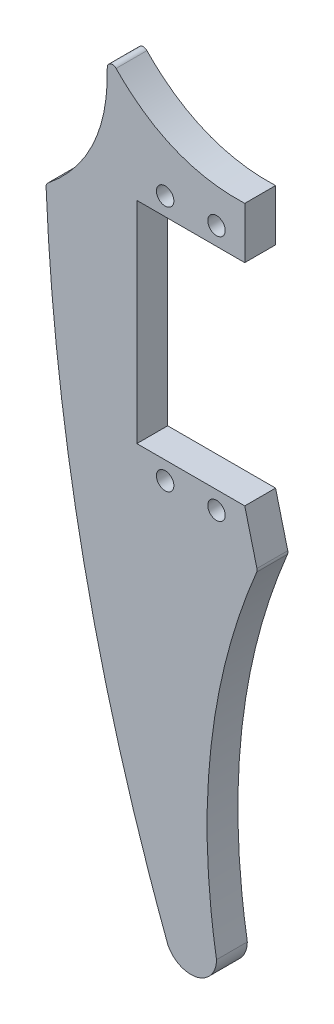
SolidWorks part; units mm, degrees
ref_plane "Front Plane" through (0, 0, 0) normal (0, 0, 1) x (1, 0, 0)
ref_plane "Top Plane" through (0, 0, 0) normal (0, 1, 0) x (1, 0, 0)
ref_plane "Right Plane" through (0, 0, 0) normal (1, 0, 0) x (0, 0, -1)
sketch "Sketch1" plane through (0, 0, 0) normal (0, 0, 1) x (1, 0, 0)
  line L0 (0, 20.5) -> (0, 10.25) construction
  line L1 (-10.5, -20.5) -> (10.5, -20.5)
  line L2 (-10.5, -20.5) -> (-10.5, 20.5)
  line L3 (-10.5, 20.5) -> (10.5, 20.5)
  line L4 (10.5, -20.5) -> (10.5, 20.5)
  line L5 (-10.5, -20.5) -> (10.5, 20.5) construction
  line L6 (-10.5, 20.5) -> (10.5, -20.5) construction
  line L7 (0, 10.25) -> (0, -99.75) construction
  line L8 (10.5, -20.5) -> (12.9541, -30.1942)
  line L9 (10.5, 20.5) -> (10.5, 30.5)
  circle A0 centre (-5, 24) radius 1.7
  circle A1 centre (5, 24) radius 1.7
  circle A2 centre (5, -24) radius 1.7
  circle A3 centre (-5, -24) radius 1.7
  circle A4 centre (0, -99.75) radius 5
  spline S0 degree 2 poles (10.5, 30.5) (-5.4634, 29.9016) (-16.4308, 42.8026) knots 0 0 0 1 1 1
  spline S1 degree 2 poles (-28.1926, 14.4749) (-25.711, -45.5894) (-4.433, -102.0628) knots 0 0 0 1 1 1
  spline S2 degree 2 poles (-16.4308, 42.8026) (-14.7841, 25.0085) (-28.1926, 14.4749) knots 0 0 0 1 1 1
  spline S3 degree 2 poles (12.9541, -30.1942) (-1.0702, -63.2681) (5, -99.75) knots 0 0 0 1 1 1
  point P0 (0, 0)
  dimension "D3" = 3.4
  dimension "D11" = 10
  dimension "D12" = 10
  dimension "D1" = 21
  dimension "D2" = 41
  dimension "D4" = 3.5
  dimension "D5" = 5
  dimension "D8" = 10.25
  dimension "D9" = 110
  dimension "D10" = 10
  dimension "D6" = 2
  dimension "D7" = 2
extrude "Boss-Extrude1" add sketch "Sketch1" along normal blind 6 contours S3 L8 L1 L2 L3 L9 S0 S2 S1 A4 A3 A2 A1 A0 | S3 A4 S1
fillet "Fillet1" radius 1 3 edges at (-28.1926, 14.4749, 3) (-16.4308, 42.8026, 3) (12.9541, -30.1942, 3)
